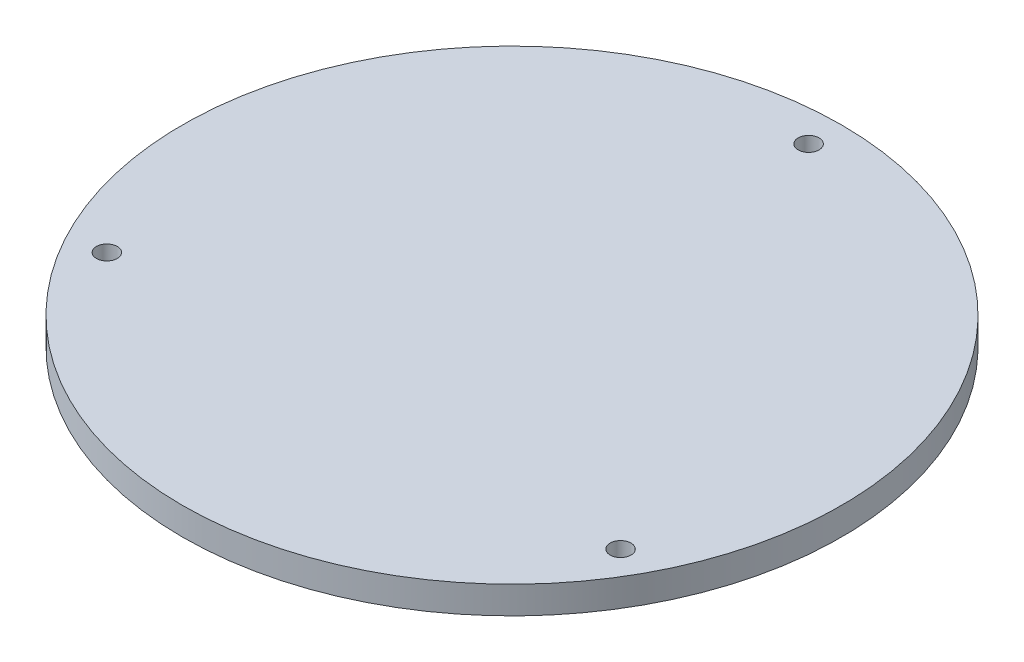
SolidWorks part; units mm, degrees
ref_plane "Front Plane" through (0, 0, 0) normal (0, 0, 1) x (1, 0, 0)
ref_plane "Top Plane" through (0, 0, 0) normal (0, 1, 0) x (1, 0, 0)
ref_plane "Right Plane" through (0, 0, 0) normal (1, 0, 0) x (0, 0, -1)
sketch "Sketch2" plane through (0, 0, 0) normal (0, 1, 0) x (1, 0, 0)
  line L0 (0, 0) -> (0, 76.2) construction
  line L1 (0, 0) -> (19.722, 73.6035) construction
  line L2 (0, 0) -> (14.1998, 52.9946) construction
  circle A0 centre (0, 0) radius 76.2
  circle A1 centre (0, 0) radius 50.8
  circle A2 centre (0, 68.58) radius 2.413
  circle A3 centre (59.392, -34.29) radius 2.413
  circle A4 centre (-59.392, -34.29) radius 2.413
  circle A5 centre (14.1998, 52.9946) radius 2.0828
  circle A6 centre (38.7947, 38.7947) radius 2.0828
  circle A7 centre (0, 0) radius 76.2
  circle A8 centre (52.9946, 14.1998) radius 2.0828
  circle A9 centre (0, 0) radius 76.2
  circle A10 centre (52.9946, -14.1998) radius 2.0828
  circle A11 centre (0, 0) radius 76.2
  circle A12 centre (38.7947, -38.7947) radius 2.0828
  circle A13 centre (0, 0) radius 76.2
  circle A14 centre (14.1998, -52.9946) radius 2.0828
  circle A15 centre (0, 0) radius 76.2
  circle A16 centre (-14.1998, -52.9946) radius 2.0828
  circle A17 centre (0, 0) radius 76.2
  circle A18 centre (-38.7947, -38.7947) radius 2.0828
  circle A19 centre (0, 0) radius 76.2
  circle A20 centre (-52.9946, -14.1998) radius 2.0828
  circle A21 centre (0, 0) radius 76.2
  circle A22 centre (-52.9946, 14.1998) radius 2.0828
  circle A23 centre (0, 0) radius 76.2
  circle A24 centre (-38.7947, 38.7947) radius 2.0828
  circle A25 centre (0, 0) radius 76.2
  circle A26 centre (-14.1998, 52.9946) radius 2.0828
  circle A27 centre (0, 0) radius 76.2
  point P12 (0, 0)
  dimension "D1" = 152.4
  dimension "D2" = 101.6
  dimension "D3" = 4.826
  dimension "D4" = 68.58
  dimension "D6" = 4.1656
  dimension "D7" = 15
  dimension "D10" = 54.864
  dimension "D5" = 3
  dimension "D9" = 12
extrude "Boss-Extrude1" add sketch "Sketch2" along normal blind 6.35 contours A0 A26 A24 A22 A20 A18 A16 A14 A12 A10 A8 A6 A5 A4 A3 A2 A1
sketch "Sketch3" plane through (0, 0, 0) normal (0, 1, 0) x (1, 0, 0)
  circle A0 centre (0, 0) radius 59.9177
extrude "Boss-Extrude2" add sketch "Sketch3" along normal through all
